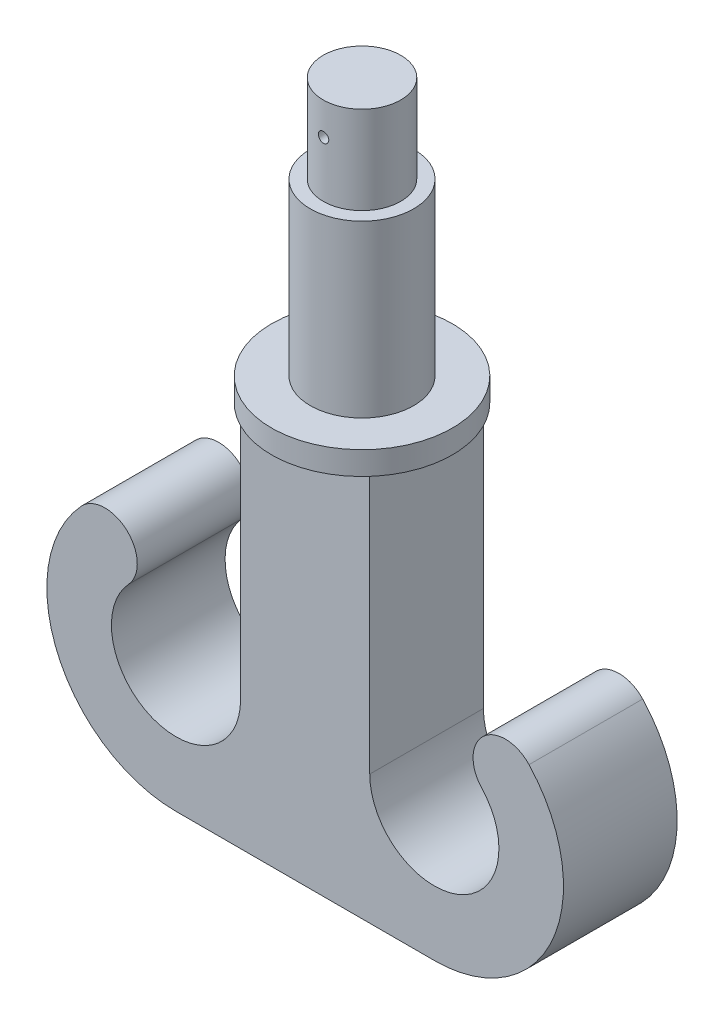
SolidWorks part; units mm, degrees
ref_plane "Front Plane" through (0, 0, 0) normal (0, 0, 1) x (1, 0, 0)
ref_plane "Top Plane" through (0, 0, 0) normal (0, 1, 0) x (1, 0, 0)
ref_plane "Right Plane" through (0, 0, 0) normal (1, 0, 0) x (0, 0, -1)
sketch "Sketch1" plane through (0, 0, 0) normal (0, 0, 1) x (1, 0, 0)
  line L0 (70.3947, 0) -> (0, 0) construction
  line L1 (0, 0) -> (0, 157.2368) construction
  line L2 (-50, 0) -> (50, 0)
  line L3 (-25, 50) -> (-25, 151)
  line L4 (25, 50) -> (25, 151)
  line L5 (-25, 151) -> (25, 151)
  arc A0 (-86.6606, 84) -> (-50, 0) centre (-50, 50) ccw
  arc A1 (-68.3303, 67) -> (-25, 50) centre (-50, 50) ccw
  arc A2 (68.3303, 67) -> (25, 50) centre (50, 50) cw
  arc A3 (86.6606, 84) -> (50, 0) centre (50, 50) cw
  arc A4 (-68.3303, 67) -> (-86.6606, 84) centre (-77.4955, 75.5) ccw
  arc A5 (68.3303, 67) -> (86.6606, 84) centre (77.4955, 75.5) cw
  point P8 (-50, 41.8475)
  point P17 (-93.4817, 101.3149)
  point P18 (0, 0)
  point P19 (-83.1075, 84.0789)
  dimension "D1" = 151
  dimension "D2" = 50
  dimension "D4" = 25.5
  dimension "D5" = 50
  dimension "D3" = 100
extrude "Boss-Extrude1" add sketch "Sketch1" along normal mid plane 44
sketch "Sketch2" plane through (0, 0, 0) normal (0, 0, 1) x (1, 0, 0)
  line L0 (0, 151) -> (35, 151)
  line L1 (25, 151) -> (-25, 151) construction
  line L2 (35, 151) -> (35, 160)
  line L3 (35, 160) -> (20, 160)
  line L4 (20, 160) -> (20, 226)
  line L5 (20, 226) -> (15, 226)
  line L6 (15, 226) -> (15, 260)
  line L7 (15, 260) -> (0, 260)
  line L8 (0, 260) -> (0, 151)
  point P7 (-595.6263, 146.4079)
  dimension "D1" = 20
  dimension "D2" = 35
  dimension "D3" = 66
  dimension "D4" = 15
  dimension "D5" = 34
  dimension "D6" = 260
revolve "Revolve1" add sketch "Sketch2" angle 360 about L8
sketch "Sketch3" plane through (0, 0, 0) normal (0, 0, 1) x (1, 0, 0)
  line L0 (15, 260) -> (-15, 260) construction
  circle A0 centre (0, 247.5) radius 2
  point P4 (0, 0)
  dimension "D1" = 4
  dimension "D2" = 12.5
extrude "Cut-Extrude1" cut sketch "Sketch3" against normal through all both and the other way through all
